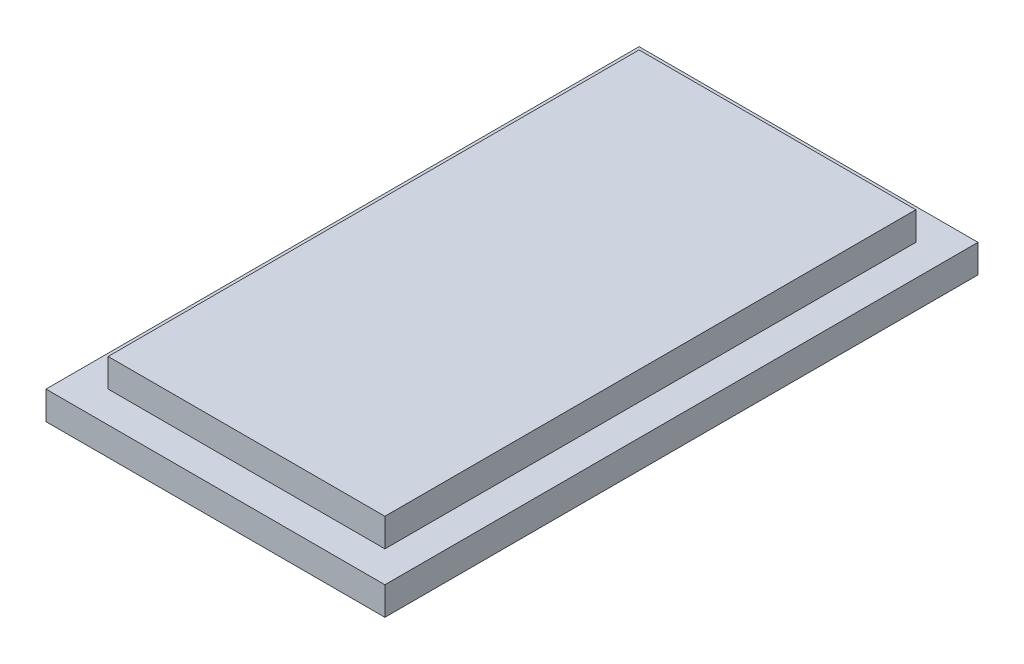
SolidWorks part; units mm, degrees
ref_plane "Front Plane" through (0, 0, 0) normal (0, 0, 1) x (1, 0, 0)
ref_plane "Top Plane" through (0, 0, 0) normal (0, 1, 0) x (1, 0, 0)
ref_plane "Right Plane" through (0, 0, 0) normal (1, 0, 0) x (0, 0, -1)
sketch "Sketch1" plane through (0, 0, 0) normal (0, 1, 0) x (1, 0, 0)
  line L1 (0, 0) -> (36, 0)
  line L2 (0, 0) -> (0, 63)
  line L3 (0, 63) -> (36, 63)
  line L4 (36, 0) -> (36, 63)
  dimension "D1" = 63
  dimension "D2" = 36
extrude "Boss-Extrude1" add sketch "Sketch1" along normal blind 3
sketch "Sketch2" plane through (0, 3, 0) normal (0, 1, 0) x (1, 0, 0)
  line L8 (3.3, 59.7) -> (3.3, 3.3)
  line L9 (3.3, 3.3) -> (32.7, 3.3)
  line L10 (32.7, 3.3) -> (32.7, 59.7)
  line L11 (32.7, 59.7) -> (3.3, 59.7)
  line L12 (3.3, 59.7) -> (3.3, 3.3)
  line L13 (3.3, 3.3) -> (32.7, 3.3)
  line L14 (32.7, 3.3) -> (32.7, 59.7)
  line L15 (32.7, 59.7) -> (3.3, 59.7)
  dimension "D1" = 3.3
extrude "Boss-Extrude2" add sketch "Sketch2" along normal blind 3
